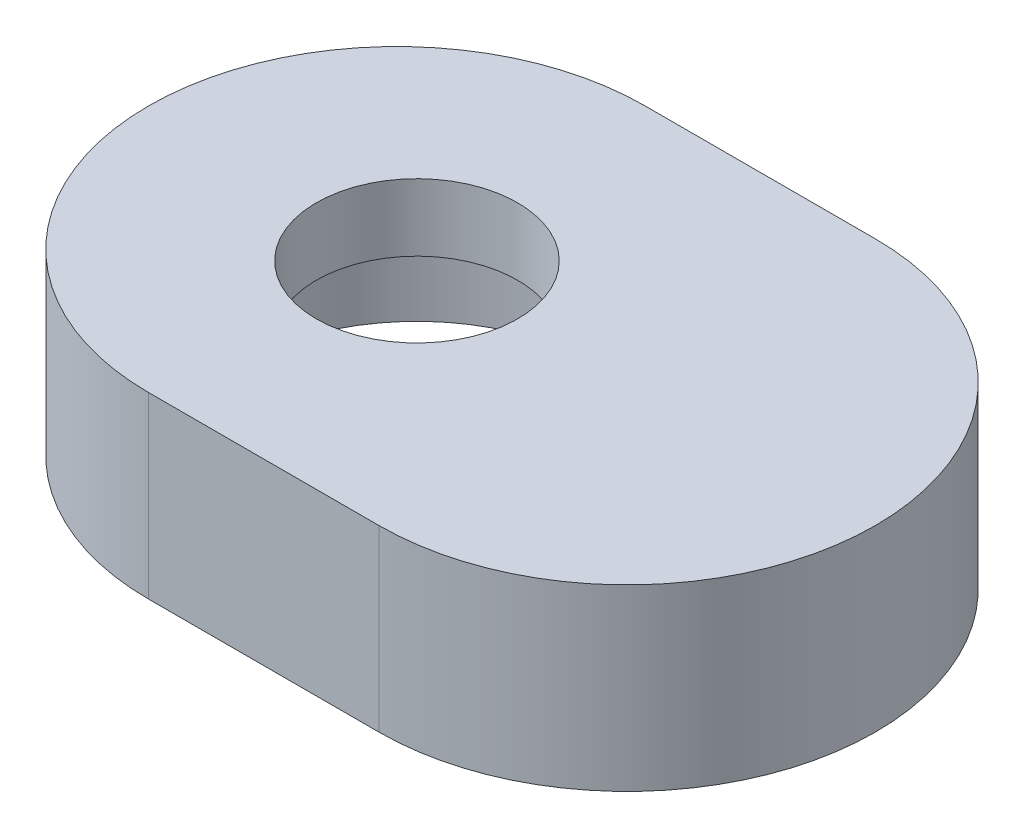
SolidWorks part; units mm, degrees
ref_plane "Front Plane" through (0, 0, 0) normal (0, 0, 1) x (1, 0, 0)
ref_plane "Top Plane" through (0, 0, 0) normal (0, 1, 0) x (1, 0, 0)
ref_plane "Right Plane" through (0, 0, 0) normal (1, 0, 0) x (0, 0, -1)
sketch "Sketch1" plane through (0, 0, 0) normal (0, 1, 0) x (1, 0, 0)
  line L0 (-5.15, 0) -> (5.15, 0) construction
  line L1 (-5.15, 11.1) -> (5.15, 11.1)
  line L2 (-5.15, -11.1) -> (5.15, -11.1)
  arc A0 (-5.15, 11.1) -> (-5.15, -11.1) centre (-5.15, 0) ccw
  arc A1 (5.15, -11.1) -> (5.15, 11.1) centre (5.15, 0) ccw
  circle A2 centre (-4.25, 0) radius 8
  point P2 (0, 0)
  point P9 (0, 0)
  dimension "D3" = 16
  dimension "D1" = 22.2
  dimension "D2" = 32.5
  dimension "D4" = 12
extrude "Boss-Extrude1" add sketch "Sketch1" along normal blind 8
sketch "Sketch2" plane through (0, 8, 0) normal (0, 1, 0) x (1, 0, 0)
  circle A0 centre (-4.25, 0) radius 8.2147
  circle A1 centre (-4.25, 0) radius 4.5
  dimension "D1" = 9
extrude "Boss-Extrude2" add sketch "Sketch2" against normal blind 3
